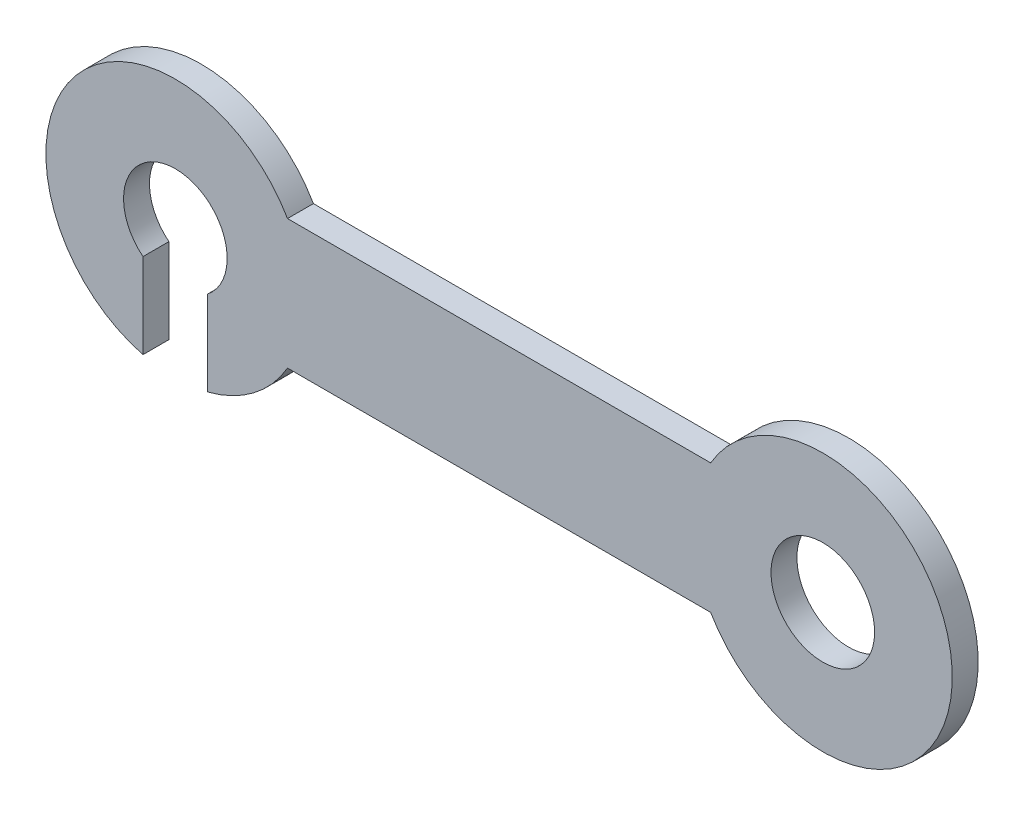
SolidWorks part; units mm, degrees
ref_plane "Front Plane" through (0, 0, 0) normal (0, 0, 1) x (1, 0, 0)
ref_plane "Top Plane" through (0, 0, 0) normal (0, 1, 0) x (1, 0, 0)
ref_plane "Right Plane" through (0, 0, 0) normal (1, 0, 0) x (0, 0, -1)
sketch "Sketch1" plane through (0, 0, 0) normal (0, 0, 1) x (1, 0, 0)
  circle A0 centre (0, 0) radius 20
  dimension "D1" = 40
extrude "Boss-Extrude1" add sketch "Sketch1" along normal blind 4
sketch "Sketch3" plane through (0, 0, 0) normal (0, 0, 1) x (1, 0, 0)
  line L0 (0, 10) -> (0, 0)
  line L1 (0, 0) -> (0, -10)
  line L2 (0, -10) -> (100, -10)
  line L3 (100, -10) -> (100, 0)
  line L4 (100, 0) -> (100, 10)
  line L5 (100, 10) -> (0, 10)
  circle A0 centre (100, 0) radius 20
  dimension "D6" = 40
  dimension "D1" = 10
  dimension "D2" = 10
  dimension "D3" = 10
  dimension "D4" = 10
  dimension "D5" = 100
extrude "Boss-Extrude2" add sketch "Sketch3" along normal blind 4 contours L2 A0 L5 L4 L3 | L5 A0 L2 L3 L4 | A0 L5 L0 L1 L2
sketch "Sketch4" plane through (0, 0, 0) normal (0, 0, 1) x (1, 0, 0)
  circle A0 centre (0, 0) radius 8
  dimension "D1" = 16
extrude "Cut-Extrude1" cut sketch "Sketch4" along normal blind 4
sketch "Sketch5" plane through (0, 0, 0) normal (0, 0, 1) x (1, 0, 0)
  line L1 (-5, -23.9724) -> (5, -23.9724)
  line L2 (-5, -23.9724) -> (-5, -4.8396)
  line L3 (-5, -4.8396) -> (5, -4.8396)
  line L4 (5, -23.9724) -> (5, -4.8396)
  line L5 (-5, -23.9724) -> (5, -4.8396) construction
  line L6 (-5, -4.8396) -> (5, -23.9724) construction
  point P0 (0, -14.406)
  dimension "D1" = 10
  dimension "D2" = 0
extrude "Cut-Extrude3" cut sketch "Sketch5" along normal blind 4
sketch "Sketch6" plane through (0, 0, 0) normal (0, 0, 1) x (1, 0, 0)
  circle A0 centre (100, 0) radius 8
  dimension "D1" = 16
extrude "Cut-Extrude4" cut sketch "Sketch6" along normal blind 4
